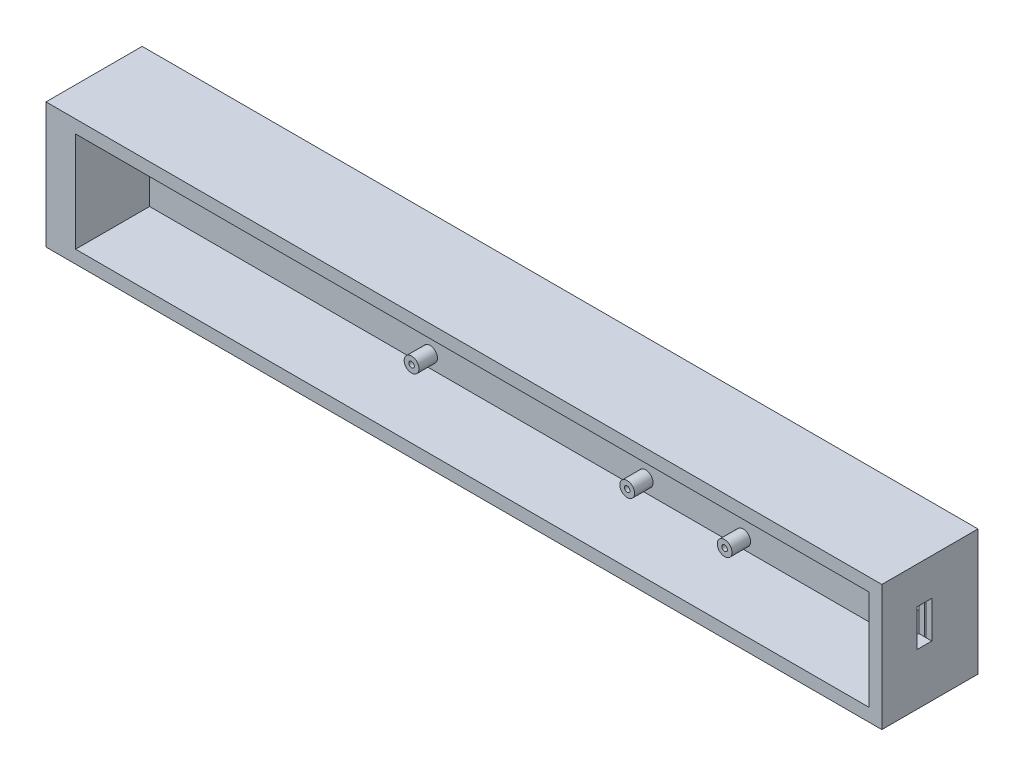
SolidWorks part; units mm, degrees
ref_plane "Спереди" through (0, 0, 0) normal (0, 0, 1) x (1, 0, 0)
ref_plane "Сверху" through (0, 0, 0) normal (0, 1, 0) x (1, 0, 0)
ref_plane "Справа" through (0, 0, 0) normal (1, 0, 0) x (0, 0, -1)
other "Configuration Table"
sketch "Эскиз1" plane through (0, 0, 0) normal (0, 0, 1) x (1, 0, 0)
  line L0 (0, 0) -> (216, 0)
  line L1 (216, 0) -> (216, 8.2)
  line L2 (216, 8.2) -> (0, 8.2)
  line L3 (0, 8.2) -> (0, 0)
  line L5 (221, 21.1) -> (221, -12.9)
  line L6 (221, -12.9) -> (-5, -12.9)
  line L8 (221, 21.1) -> (-5, 21.1)
  line L9 (-5, 21.1) -> (-5, -12.9)
  line L10 (0, 4.1) -> (-40.481, 4.1) construction
  line L11 (108, 21.1) -> (108, 56.679) construction
  line L12 (108, 8.2) -> (108, -37.8381) construction
  dimension "D1" = 216
  dimension "D2" = 8.2
  dimension "D3" = 34
  dimension "D4" = 17
  dimension "D5" = 226
  dimension "D6" = 113
extrude "Бобышка-Вытянуть1" add sketch "Эскиз1" along normal blind 6
sketch "Эскиз2" plane through (0, 0, 6) normal (0, 0, 1) x (1, 0, 0)
  line L0 (108, 21.1) -> (108, -27.0607) construction
  line L1 (221, 21.1) -> (-5, 21.1) construction
  line L2 (0, 4.1) -> (196.361, 4.1) construction
  line L3 (0, 8.2) -> (0, 0) construction
  circle A0 centre (78.85, 14.2) radius 2
  circle A1 centre (78.85, -6) radius 2
  circle A2 centre (137.15, 14.2) radius 2
  circle A3 centre (137.15, -6) radius 2
  dimension "D9" = 4
  dimension "D10" = 4
  dimension "D11" = 4
  dimension "D12" = 4
  dimension "D1" = 29.15
  dimension "D2" = 29.15
  dimension "D3" = 29.15
  dimension "D4" = 29.15
  dimension "D5" = 10.1
  dimension "D6" = 10.1
  dimension "D7" = 10.1
  dimension "D8" = 10.1
extrude "Бобышка-Вытянуть2" add sketch "Эскиз2" along normal blind 5
sketch "Эскиз3" plane through (0, 0, 11) normal (0, 0, 1) x (1, 0, 0)
  circle A0 centre (78.85, 14.2) radius 0.75
  circle A1 centre (78.85, -6) radius 0.75
  circle A2 centre (137.15, 14.2) radius 0.75
  circle A3 centre (137.15, -6) radius 0.75
  dimension "D1" = 1.5
  dimension "D2" = 1.5
  dimension "D3" = 1.5
  dimension "D4" = 1.5
extrude "Вырез-Вытянуть1" cut sketch "Эскиз3" against normal blind 5
sketch "Эскиз4" plane through (0, 0, 6) normal (0, 0, 1) x (1, 0, 0)
  line L0 (-5, 21.1) -> (221, 21.1)
  line L1 (221, 21.1) -> (221, -12.9)
  line L2 (221, -12.9) -> (-5, -12.9)
  line L3 (-5, -12.9) -> (-5, 21.1)
  line L4 (3, 17.6) -> (3, -9.4)
  line L5 (3, -9.4) -> (213, -9.4)
  line L6 (213, -9.4) -> (213, 17.6)
  line L7 (213, 17.6) -> (3, 17.6)
  line L8 (0, 4.1) -> (224.8919, 4.1) construction
  line L9 (0, 8.2) -> (0, 0) construction
  dimension "D1" = 27
  dimension "D2" = 13.5
  dimension "D3" = 8
  dimension "D4" = 8
extrude "Бобышка-Вытянуть3" add sketch "Эскиз4" along normal blind 2
sketch "Эскиз5" plane through (0, 0, 6) normal (0, 0, 1) x (1, 0, 0)
  line L0 (216.8019, 21.1) -> (216.8019, -12.9) construction
  line L1 (221, 21.1) -> (-5, 21.1) construction
  line L2 (-5, -12.9) -> (221, -12.9) construction
sketch "Эскиз6" plane through (0, 0, 8) normal (0, 0, 1) x (1, 0, 0)
  line L0 (-5, 21.1) -> (221, 21.1)
  line L1 (221, 21.1) -> (221, -12.9)
  line L2 (221, -12.9) -> (-5, -12.9)
  line L3 (-5, -12.9) -> (-5, 21.1)
  line L4 (3, 17.6) -> (217.5, 17.6)
  line L8 (3, -9.4) -> (3, 17.6)
  line L9 (3, -9.4) -> (217.5, -9.4)
  line L10 (217.5, -9.4) -> (217.5, 17.6)
  dimension "D1" = 3.5
extrude "Бобышка-Вытянуть4" add sketch "Эскиз6" along normal blind 18
sketch "Эскиз7" plane through (217.5, 0, 0) normal (-1, 0, 0) x (0, 0, 1)
  line L0 (11, 17.6) -> (11, -9.4)
  line L1 (26, 17.6) -> (6, 17.6) construction
  line L2 (26, -9.4) -> (6, -9.4) construction
  line L3 (11, -9.4) -> (12.5, -9.4)
  line L4 (12.5, -9.4) -> (12.5, 17.6)
  line L5 (12.5, 17.6) -> (11, 17.6)
  line L6 (8, -9.4) -> (8, 17.6) construction
  dimension "D1" = 3
  dimension "D2" = 1.5
extrude "Вырез-Вытянуть2" cut sketch "Эскиз7" against normal blind 2
sketch "Эскиз8" plane through (0, 0, 6) normal (0, 0, 1) x (1, 0, 0)
  line L0 (219.5, -9.4) -> (219.5, 17.6) construction
  line L1 (216, 4.1) -> (148.1179, 4.1) construction
  line L2 (216, 0) -> (216, 8.2) construction
  circle A0 centre (163.5, 14.85) radius 2
  circle A1 centre (163.5, -6.65) radius 2
  dimension "D5" = 4
  dimension "D6" = 4
  dimension "D1" = 56
  dimension "D2" = 56
  dimension "D3" = 10.75
  dimension "D4" = 10.75
extrude "Бобышка-Вытянуть5" add sketch "Эскиз8" along normal blind 5
sketch "Эскиз9" plane through (0, 0, 11) normal (0, 0, 1) x (1, 0, 0)
  circle A0 centre (163.5, 14.85) radius 0.75
  circle A1 centre (163.5, -6.65) radius 0.75
  dimension "D1" = 1.5
  dimension "D2" = 1.5
extrude "Вырез-Вытянуть3" cut sketch "Эскиз9" against normal blind 5
sketch "Эскиз10" plane through (217.5, 0, 0) normal (-1, 0, 0) x (0, 0, 1)
  line L0 (12.5, 11.1) -> (16.5, 11.1)
  line L1 (12.5, -9.4) -> (12.5, 17.6) construction
  line L5 (12.5, 4.1) -> (9.1271, 4.1) construction
  line L6 (16.5, 11.1) -> (16.5, 1.1)
  line L7 (16.5, 1.1) -> (12.5, 1.1)
  line L8 (12.5, 1.1) -> (12.5, 11.1)
  dimension "D1" = 4
  dimension "D2" = 3
  dimension "D3" = 7
extrude "Вырез-Вытянуть4" cut sketch "Эскиз10" against normal blind 5
